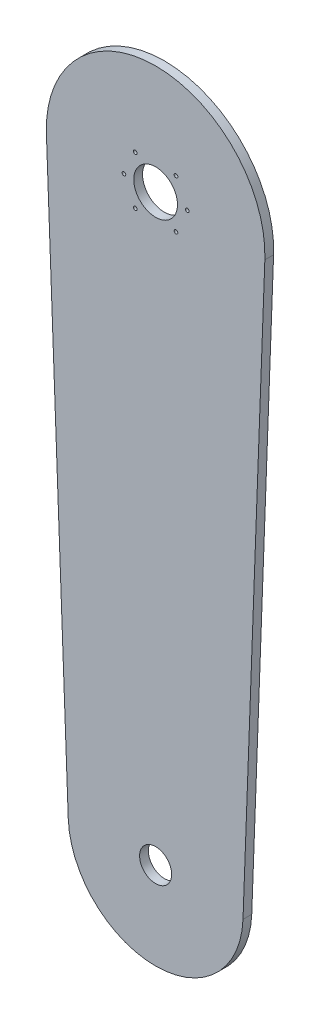
SolidWorks part; units mm, degrees
ref_plane "前视基准面" through (0, 0, 0) normal (0, 0, 1) x (1, 0, 0)
ref_plane "上视基准面" through (0, 0, 0) normal (0, 1, 0) x (1, 0, 0)
ref_plane "右视基准面" through (0, 0, 0) normal (1, 0, 0) x (0, 0, -1)
other "Configuration Table"
sketch "草图1" plane through (0, 0, 0) normal (0, 0, 1) x (1, 0, 0)
  line L0 (0, 435.7923) -> (0, -629.8791) construction
  line L1 (-74.9472, -2.8125) -> (-59.9578, -402.25)
  line L2 (74.9472, -2.8125) -> (59.9578, -402.25)
  arc A0 (74.9472, -2.8125) -> (-74.9472, -2.8125) centre (0, 0) ccw
  arc A1 (-59.9578, -402.25) -> (59.9578, -402.25) centre (0, -400) ccw
  circle A2 centre (0, 0) radius 15
  circle A3 centre (0, -400) radius 11
  dimension "D1" = 120
  dimension "D2" = 150
  dimension "D4" = 30
  dimension "D5" = 22
  dimension "D3" = 400
extrude "凸台-拉伸1" add sketch "草图1" along normal blind 6 contours L0 A3 | A3 L0 | A2 L0 | L0 A2 | L2 A1 L1 A0
sketch "草图2" plane through (0, 0, 6) normal (0, 0, 1) x (1, 0, 0)
  line L0 (0, 0) -> (0, 62.2671) construction
  line L1 (0, 0) -> (36.6183, 43.64) construction
  line L2 (0, 0) -> (53.4831, 0) construction
  line L3 (0, 0) -> (-43.4326, 0) construction
  circle A8 centre (13.9806, 16.6615) radius 1.25
  circle A9 centre (21.75, 0) radius 1.25
  circle A10 centre (13.9806, -16.6615) radius 1.25
  circle A11 centre (-13.9806, 16.6615) radius 1.25
  circle A12 centre (-21.75, 0) radius 1.25
  circle A13 centre (-13.9806, -16.6615) radius 1.25
  dimension "D1" = 50
  dimension "D2" = 2.5
  dimension "D3" = 2.5
  dimension "D4" = 21.75
  dimension "D5" = 21.75
extrude "切除-拉伸1" cut sketch "草图2" against normal mid plane 20
equation "\"、\"=6"
